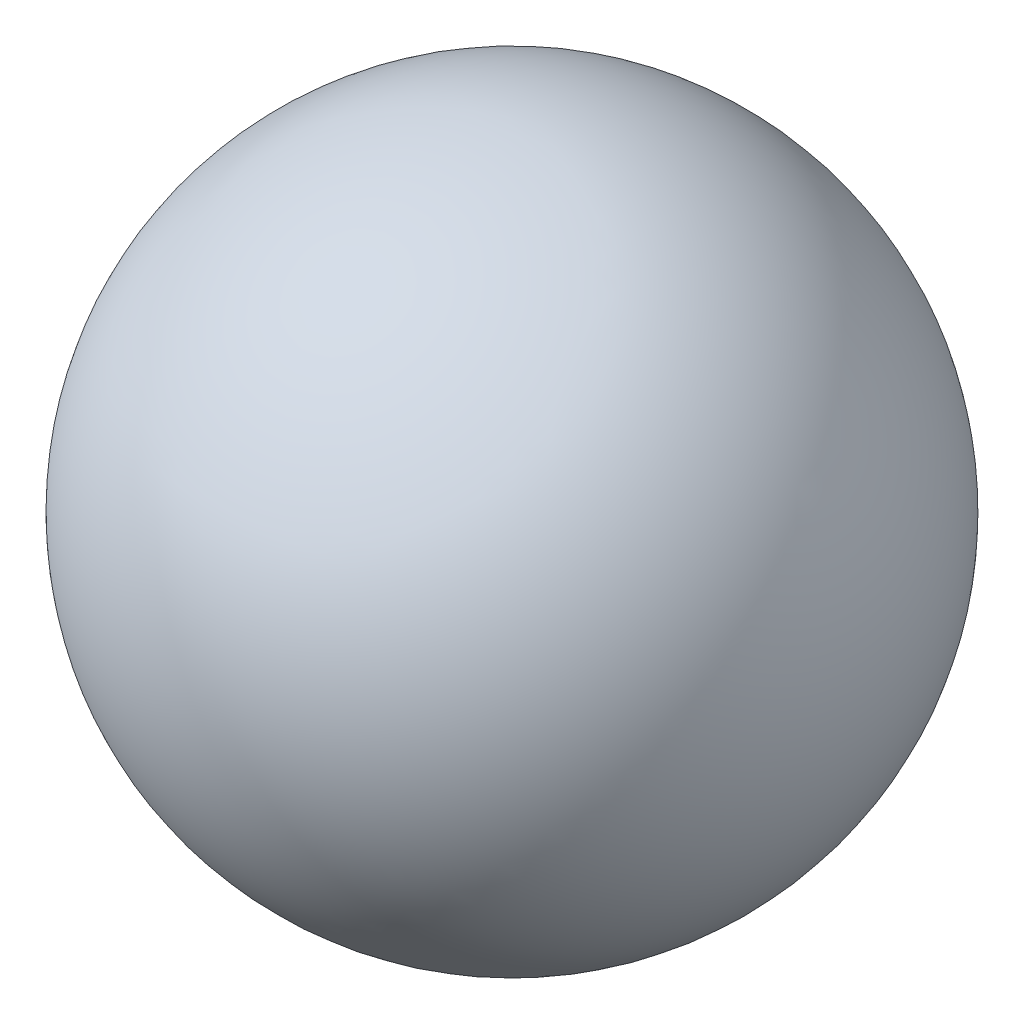
SolidWorks part; units mm, degrees
ref_plane "Front Plane" through (0, 0, 0) normal (0, 0, 1) x (1, 0, 0)
ref_plane "Top Plane" through (0, 0, 0) normal (0, 1, 0) x (1, 0, 0)
ref_plane "Right Plane" through (0, 0, 0) normal (1, 0, 0) x (0, 0, -1)
sketch "Sketch1" plane through (0, 0, 0) normal (0, 0, 1) x (1, 0, 0)
  line L0 (-2.7799, -1.605) -> (-4.0941, -2.3638)
  line L1 (-2.7037, -1.561) -> (-4.2584, -2.4586) construction
  arc A0 (-4.0941, -2.3638) -> (-2.7799, -1.605) centre (-3.437, -1.9844) ccw
revolve "Revolve1" add sketch "Sketch1" angle 360 about L1
